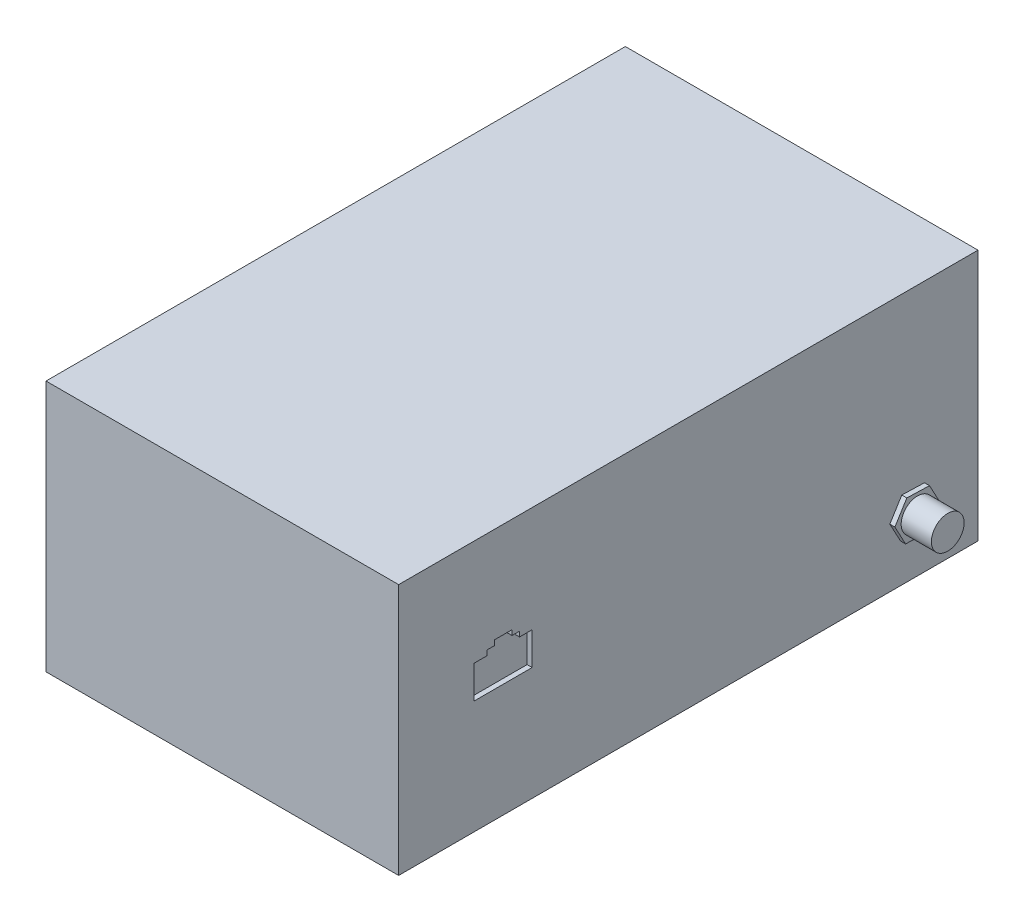
SolidWorks part; units mm, degrees
ref_plane "前视基准面" through (0, 0, 0) normal (0, 0, 1) x (1, 0, 0)
ref_plane "上视基准面" through (0, 0, 0) normal (0, 1, 0) x (1, 0, 0)
ref_plane "右视基准面" through (0, 0, 0) normal (1, 0, 0) x (0, 0, -1)
sketch "草图1" plane through (0, 0, 0) normal (0, 0, 1) x (1, 0, 0)
  line L1 (35, -25) -> (-35, -25)
  line L2 (35, -25) -> (35, 25)
  line L3 (35, 25) -> (-35, 25)
  line L4 (-35, -25) -> (-35, 25)
  line L5 (35, -25) -> (-35, 25) construction
  line L6 (35, 25) -> (-35, -25) construction
  point P0 (0, 0)
  dimension "D1" = 70
  dimension "D2" = 50
extrude "凸台-拉伸1" add sketch "草图1" along normal blind 115
sketch "草图2" plane through (35, 0, 0) normal (1, 0, 0) x (0, 0, -1)
  line L0 (-94.25, -2.5) -> (-94.25, 19.406) construction
  line L1 (-100, -2.5) -> (-88.5, -2.5)
  line L2 (-100, -2.5) -> (-100, 4)
  line L3 (-100, 4) -> (-97.5, 4)
  line L4 (-88.5, -2.5) -> (-88.5, 4)
  line L5 (-100, -2.5) -> (-88.5, 4) construction
  line L6 (-100, 4) -> (-88.5, -2.5) construction
  line L7 (-115, 25) -> (0, 25) construction
  line L8 (-97.5, 4) -> (-97.5, 5)
  line L9 (-97.5, 5) -> (-96, 5)
  line L10 (-91, 4) -> (-91, 5)
  line L11 (-115, -25) -> (-115, 25) construction
  line L12 (-92.5, 5) -> (-92.5, 6)
  line L13 (-92.5, 6) -> (-96, 6)
  line L14 (-96, 5) -> (-96, 6)
  line L15 (-91, 4) -> (-88.5, 4)
  line L16 (-92.5, 5) -> (-91, 5)
  point P0 (-94.25, 0.75)
  dimension "D1" = 11.5
  dimension "D2" = 6.5
  dimension "D3" = 6.5
  dimension "D4" = 1
  dimension "D5" = 3.5
  dimension "D6" = 1
  dimension "D7" = 19
  dimension "D8" = 15
extrude "切除-拉伸1" cut sketch "草图2" against normal blind 1
sketch "草图3" plane through (35, 0, 0) normal (1, 0, 0) x (0, 0, -1)
  line L0 (-115, -25) -> (0, -25) construction
  line L1 (-15.125, -9.5333) -> (-17.4977, -13.357)
  line L2 (-17.4977, -13.357) -> (-15.3727, -17.3236)
  line L3 (-15.3727, -17.3236) -> (-10.875, -17.4667)
  line L4 (-10.875, -17.4667) -> (-8.5023, -13.643)
  line L5 (-8.5023, -13.643) -> (-10.6273, -9.6764)
  line L6 (-10.6273, -9.6764) -> (-15.125, -9.5333)
  line L7 (0, -25) -> (0, 25) construction
  circle A0 centre (-13, -13.5) radius 4.5 construction
  dimension "D1" = 11.5
  dimension "D2" = 13
extrude "凸台-拉伸2" add sketch "草图3" along normal blind 1
sketch "草图4" plane through (36, 0, 0) normal (1, 0, 0) x (0, 0, -1)
  line L0 (-12.8761, -9.6049) -> (-13.1239, -17.3951) construction
  line L1 (-10.6273, -9.6764) -> (-15.125, -9.5333) construction
  line L2 (-15.3727, -17.3236) -> (-10.875, -17.4667) construction
  circle A0 centre (-13, -13.5) radius 3.25
  dimension "D1" = 6.5
extrude "凸台-拉伸3" add sketch "草图4" along normal blind 6
sketch "草图5" plane through (0, 0, 0) normal (0, 0, -1) x (-1, 0, 0)
  line L0 (35, 25) -> (35, -25) construction
  line L1 (24.8971, -18.25) -> (24.8971, -13.75)
  line L2 (24.8971, -13.75) -> (21, -11.5)
  line L3 (21, -11.5) -> (17.1029, -13.75)
  line L4 (17.1029, -13.75) -> (17.1029, -18.25)
  line L5 (17.1029, -18.25) -> (21, -20.5)
  line L6 (21, -20.5) -> (24.8971, -18.25)
  line L7 (35, -25) -> (-35, -25) construction
  circle A0 centre (21, -16) radius 4.5 construction
  dimension "D1" = 9
  dimension "D2" = 14
  dimension "D3" = 9
extrude "凸台-拉伸4" add sketch "草图5" along normal blind 1
sketch "草图6" plane through (0, 0, -1) normal (0, 0, -1) x (-1, 0, 0)
  line L0 (22.9486, -12.625) -> (19.0514, -19.375) construction
  line L1 (24.8971, -13.75) -> (21, -11.5) construction
  line L2 (17.1029, -18.25) -> (21, -20.5) construction
  circle A0 centre (21, -16) radius 3.25
  dimension "D1" = 6.5
extrude "凸台-拉伸5" add sketch "草图6" along normal blind 6
sketch "草图7" plane through (0, 0, 0) normal (0, 0, -1) x (-1, 0, 0)
  line L0 (-18.25, -2.5) -> (-18.25, 14.1175) construction
  line L1 (-24, 4) -> (-21.25, 4)
  line L2 (-24, 4) -> (-24, -2.5)
  line L3 (-24, -2.5) -> (-12.5, -2.5)
  line L4 (-12.5, 4) -> (-12.5, -2.5)
  line L6 (-21.25, 4) -> (-21.25, 5)
  line L7 (-21.25, 5) -> (-20.25, 5)
  line L8 (-15.25, 4) -> (-15.25, 5)
  line L10 (-20.25, 5) -> (-20.25, 6)
  line L11 (-20.25, 6) -> (-16.25, 6)
  line L12 (-16.25, 5) -> (-16.25, 6)
  line L13 (-35, 25) -> (35, 25) construction
  line L14 (-35, -25) -> (-35, 25) construction
  line L15 (-15.25, 4) -> (-12.5, 4)
  line L16 (-16.25, 5) -> (-15.25, 5)
  dimension "D1" = 6.5
  dimension "D2" = 11.5
  dimension "D3" = 6
  dimension "D4" = 4
  dimension "D5" = 1
  dimension "D6" = 1
  dimension "D7" = 19
  dimension "D8" = 11
extrude "切除-拉伸2" cut sketch "草图7" against normal blind 1
hole_wizard "M3 螺纹孔的螺纹孔钻头1" positions "草图8" profile "草图9" hole size "M3" standard "GB"
sketch "草图8" plane through (-35, 0, 0) normal (-1, 0, 0) x (0, 0, 1)
  line L0 (0, 25) -> (0, -25) construction
  line L1 (115, 0) -> (35.1936, 0) construction
  line L2 (115, 25) -> (115, -25) construction
  point P0 (55, -9)
  point P2 (55, 9)
  dimension "D1" = 55
  dimension "D2" = 18
sketch "草图9" plane through (-35, -9, 55) normal (0, 1, 0) x (0, 0, 1)
  line L0 (0, 0) -> (0, 2.7511)
  line L1 (0, 2.7511) -> (1.25, 2)
  line L2 (1.25, 2) -> (1.25, 0)
  line L5 (1.25, 0) -> (0, 0)
  line L10 (0, 2.7511) -> (-1.25, 2) construction
  line L11 (0, -6.35) -> (0, 107.95) construction
  dimension "孔直径" = 2.5
  dimension "孔深度" = 2
  dimension "导头角度" = 118
sketch "草图10" plane through (0, 0, 0) normal (0, 0, -1) x (-1, 0, 0)
  line L1 (19.2851, -5) -> (-5.7149, -5)
  line L2 (19.2851, -5) -> (19.2851, 5)
  line L3 (19.2851, 5) -> (-5.7149, 5)
  line L4 (-5.7149, -5) -> (-5.7149, 5)
  line L5 (19.2851, -5) -> (-5.7149, 5) construction
  line L6 (19.2851, 5) -> (-5.7149, -5) construction
  point P0 (6.7851, 0)
  dimension "D1" = 10
  dimension "D2" = 25
extrude "凸台-拉伸6" add sketch "草图10" along normal blind 2
